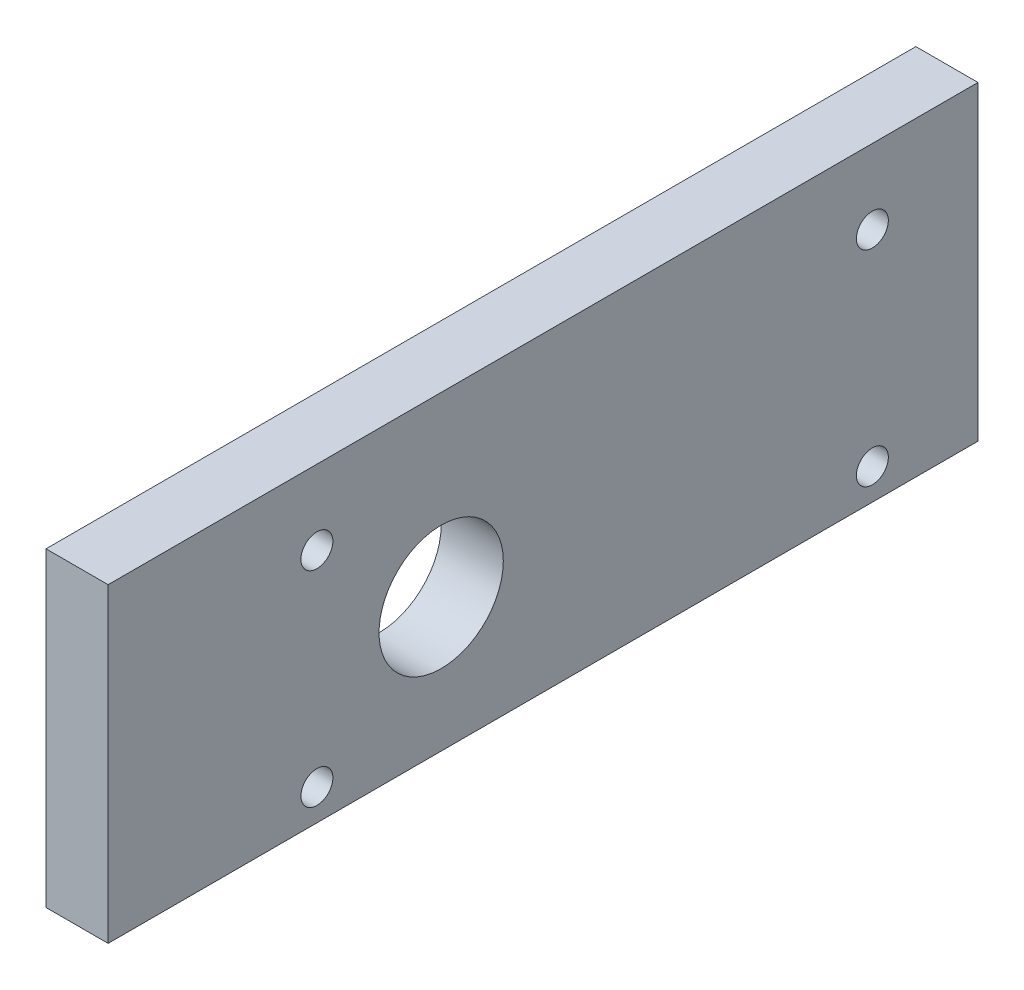
SolidWorks part; units mm, degrees
ref_plane "Front Plane" through (0, 0, 0) normal (0, 0, 1) x (1, 0, 0)
ref_plane "Top Plane" through (0, 0, 0) normal (0, 1, 0) x (1, 0, 0)
ref_plane "Right Plane" through (0, 0, 0) normal (1, 0, 0) x (0, 0, -1)
sketch "Sketch1" plane through (0, 0, 0) normal (1, 0, 0) x (0, 0, -1)
  line L1 (-44.45, -15.875) -> (44.45, -15.875)
  line L2 (-44.45, -15.875) -> (-44.45, 15.875)
  line L3 (-44.45, 15.875) -> (44.45, 15.875)
  line L4 (44.45, -15.875) -> (44.45, 15.875)
  line L5 (-44.45, -15.875) -> (44.45, 15.875) construction
  line L6 (-44.45, 15.875) -> (44.45, -15.875) construction
  point P0 (0, 0)
  dimension "D1" = 88.9
  dimension "D2" = 31.75
extrude "Boss-Extrude1" add sketch "Sketch1" along normal mid plane 6.35
sketch "Sketch2" plane through (3.175, 0, 0) normal (1, 0, 0) x (0, 0, -1)
  line L0 (44.45, -15.875) -> (44.45, 15.875) construction
  line L1 (-23.114, -12.7) -> (33.655, -12.7) construction
  line L2 (-23.114, -12.7) -> (-23.114, 8.255) construction
  line L3 (-23.114, 8.255) -> (33.655, 8.255) construction
  line L4 (33.655, -12.7) -> (33.655, 8.255) construction
  line L5 (-23.114, -12.7) -> (33.655, 8.255) construction
  line L6 (-23.114, 8.255) -> (33.655, -12.7) construction
  line L7 (-44.45, -15.875) -> (44.45, -15.875) construction
  line L8 (5.2705, -2.2225) -> (-10.414, -2.2225) construction
  circle A0 centre (-23.114, 8.255) radius 1.632
  circle A1 centre (-23.114, -12.7) radius 1.632
  circle A2 centre (33.655, -12.7) radius 1.6319
  circle A3 centre (33.655, 8.255) radius 1.6319
  circle A4 centre (-10.414, -2.2225) radius 6.35
  point P0 (5.2705, -2.2225)
  point P3 (5.2705, -2.2225)
  dimension "D5" = 3.2639
  dimension "D6" = 15.6845
  dimension "D7" = 12.7
  dimension "D1" = 56.769
  dimension "D2" = 20.955
  dimension "D3" = 10.795
  dimension "D4" = 3.175
extrude "Cut-Extrude1" cut sketch "Sketch2" against normal up to next
